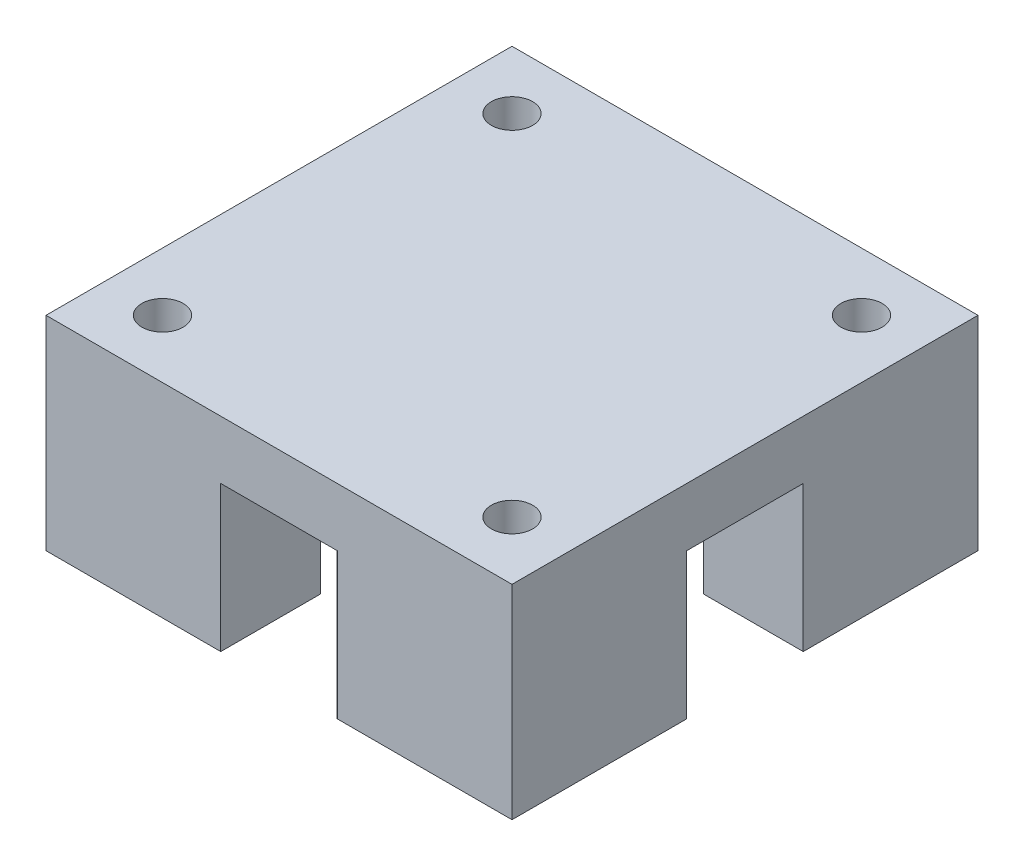
SolidWorks part; units mm, degrees
material "Copper"
ref_plane "Front Plane" through (0, 0, 0) normal (0, 0, 1) x (1, 0, 0)
ref_plane "Top Plane" through (0, 0, 0) normal (0, 1, 0) x (1, 0, 0)
ref_plane "Right Plane" through (0, 0, 0) normal (1, 0, 0) x (0, 0, -1)
sketch "Sketch1" plane through (0, 0, 0) normal (0, 1, 0) x (1, 0, 0)
  line L1 (-25.4, 25.4) -> (25.4, 25.4)
  line L2 (-25.4, 25.4) -> (-25.4, -25.4)
  line L3 (-25.4, -25.4) -> (25.4, -25.4)
  line L4 (25.4, 25.4) -> (25.4, -25.4)
  line L5 (-25.4, 25.4) -> (25.4, -25.4) construction
  line L6 (-25.4, -25.4) -> (25.4, 25.4) construction
  point P0 (0, 0)
  dimension "D1" = 50.8
  dimension "D2" = 50.8
extrude "Boss-Extrude1" add sketch "Sketch1" along normal blind 22.225
hole_wizard "#8 Clearance Hole1" positions "Sketch8" profile "Sketch7" hole size "#8" standard "ANSI Inch" end condition through all
sketch "Sketch8" plane through (0, 22.225, 0) normal (0, 1, 0) x (1, 0, 0)
  point P0 (-19.05, 19.05)
  point P2 (19.05, 19.05)
  point P4 (19.05, -19.05)
  point P6 (-19.05, -19.05)
  dimension "D1" = 19.05
  dimension "D2" = 19.05
  dimension "D3" = 19.05
  dimension "D4" = 19.05
sketch "Sketch7" plane through (-19.05, 22.225, -19.05) normal (1, 0, 0) x (0, 0, 1)
  line L0 (0, 0) -> (0, 22.225)
  line L1 (0, 22.225) -> (2.2479, 22.225)
  line L2 (2.2479, 22.225) -> (2.2479, 0)
  line L5 (2.2479, 0) -> (0, 0)
  line L11 (0, -6.35) -> (0, 107.95) construction
  dimension "Thru Hole Dia." = 4.4958
  dimension "Thru Hole Depth" = 22.225
sketch "Sketch9" plane through (0, 0, 0) normal (0, -1, 0) x (1, 0, 0)
  line L0 (-25.4, -25.4) -> (-25.4, 25.4) construction
  line L1 (-25.4, 6.35) -> (25.4, 6.35)
  line L2 (-25.4, 6.35) -> (-25.4, -6.35)
  line L3 (-25.4, -6.35) -> (25.4, -6.35)
  line L4 (25.4, 6.35) -> (25.4, -6.35)
  line L5 (25.4, 25.4) -> (25.4, -25.4) construction
  line L6 (-25.4, 25.4) -> (25.4, 25.4) construction
  line L7 (-6.35, 25.4) -> (6.35, 25.4)
  line L8 (-6.35, 25.4) -> (-6.35, -25.4)
  line L9 (-6.35, -25.4) -> (6.35, -25.4)
  line L10 (6.35, 25.4) -> (6.35, -25.4)
  line L11 (25.4, -25.4) -> (-25.4, -25.4) construction
  circle A0 centre (0, 0) radius 15.875
  line M5 (25.4, -25.4) -> (25.4, 25.4)
  line M6 (25.4, 25.4) -> (-25.4, 25.4)
  line M7 (-25.4, 25.4) -> (-25.4, -25.4)
  line M8 (-25.4, -25.4) -> (25.4, -25.4)
  dimension "D1" = 12.7
  dimension "D3" = 31.75
  dimension "D2" = 12.7
  dimension "D4" = 6.35
  dimension "D5" = 6.35
extrude "Cut-Extrude1" cut sketch "Sketch9" against normal blind 15.875 contours L8 A0 L1 | A0 L10 L8 M6 | L1 A0 L10 | A0 L3 L1 M5 | L10 A0 L3 | A0 L8 L10 M8 | L3 A0 L8 | A0 L1 L3 M7 | L1 A0 L3 L8 | L8 A0 L10 L3 | L3 A0 L1 L10 | L10 L1 L8 L3 | L10 A0 L8 L1
